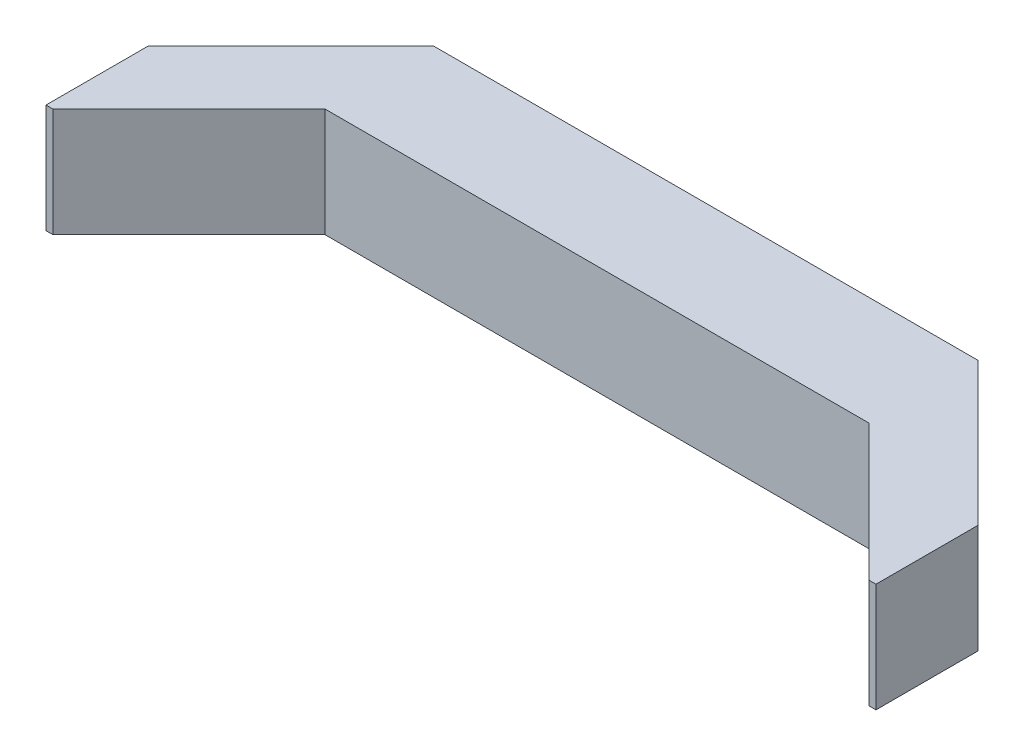
SolidWorks part; units mm, degrees
ref_plane "Front Plane" through (0, 0, 0) normal (0, 0, 1) x (1, 0, 0)
ref_plane "Top Plane" through (0, 0, 0) normal (0, 1, 0) x (1, 0, 0)
ref_plane "Right Plane" through (0, 0, 0) normal (1, 0, 0) x (0, 0, -1)
sketch "Sketch1" plane through (0, 0, 0) normal (0, 0, 1) x (1, 0, 0)
  line L0 (2032, 406.4) -> (0, 406.4)
  line L1 (0, 0) -> (2032, 0)
  line L2 (0, 0) -> (0, 406.4)
  line L4 (2032, 0) -> (2032, 406.4)
  dimension "D1" = 2032
  dimension "D2" = 406.4
extrude "Boss-Extrude1" add sketch "Sketch1" along normal blind 406.4
sketch "Sketch8" plane through (0, 406.4, 0) normal (0, 1, 0) x (1, 0, 0)
  line L0 (0, -406.4) -> (-508, -914.4)
  line L1 (-508, -914.4) -> (-533.4, -914.4)
  line L2 (-533.4, -914.4) -> (-533.4, -533.4)
  line L3 (-533.4, -533.4) -> (0, 0)
  line L4 (0, -406.4) -> (0, 0) construction
  line L5 (0, -406.4) -> (0, 0)
  dimension "D1" = 135
  dimension "D2" = 508
  dimension "D3" = 381
  dimension "D4" = 135
extrude "Boss-Extrude2" add sketch "Sketch8" against normal blind 406.4
ref_plane "Plane1" through (1016, 0, 0) normal (1, 0, 0) x (0, 0, -1)
mirror "Mirror1" about plane through (1016, 0, 0) normal (1, 0, 0) of "Boss-Extrude2"
